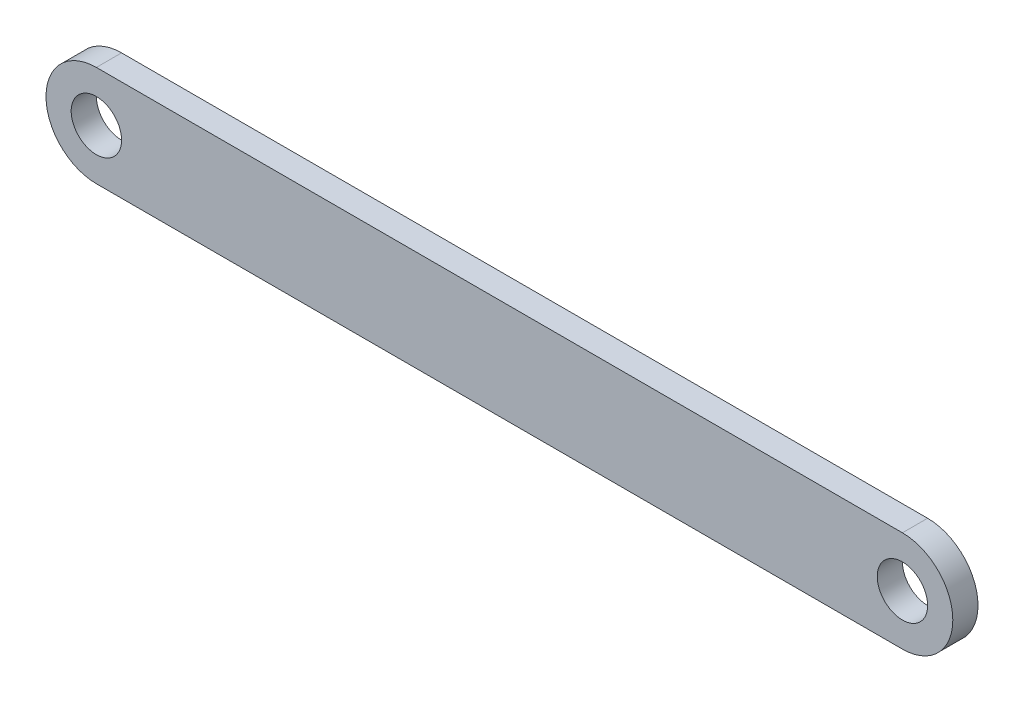
SolidWorks part; units mm, degrees
ref_plane "Front Plane" through (0, 0, 0) normal (0, 0, 1) x (1, 0, 0)
ref_plane "Top Plane" through (0, 0, 0) normal (0, 1, 0) x (1, 0, 0)
ref_plane "Right Plane" through (0, 0, 0) normal (1, 0, 0) x (0, 0, -1)
sketch "Sketch1" plane through (0, 0, 0) normal (0, 0, 1) x (1, 0, 0)
  line L0 (80, 0) -> (-80, 0) construction
  line L1 (80, -10) -> (-80, -10)
  line L2 (80, 10) -> (-80, 10)
  arc A0 (80, -10) -> (80, 10) centre (80, 0) ccw
  arc A1 (-80, 10) -> (-80, -10) centre (-80, 0) ccw
  circle A2 centre (80, 0) radius 5
  circle A3 centre (-80, 0) radius 5
  point P2 (0, 0)
  dimension "D1" = 160
  dimension "D2" = 20
extrude "Boss-Extrude1" add sketch "Sketch1" along normal blind 5
